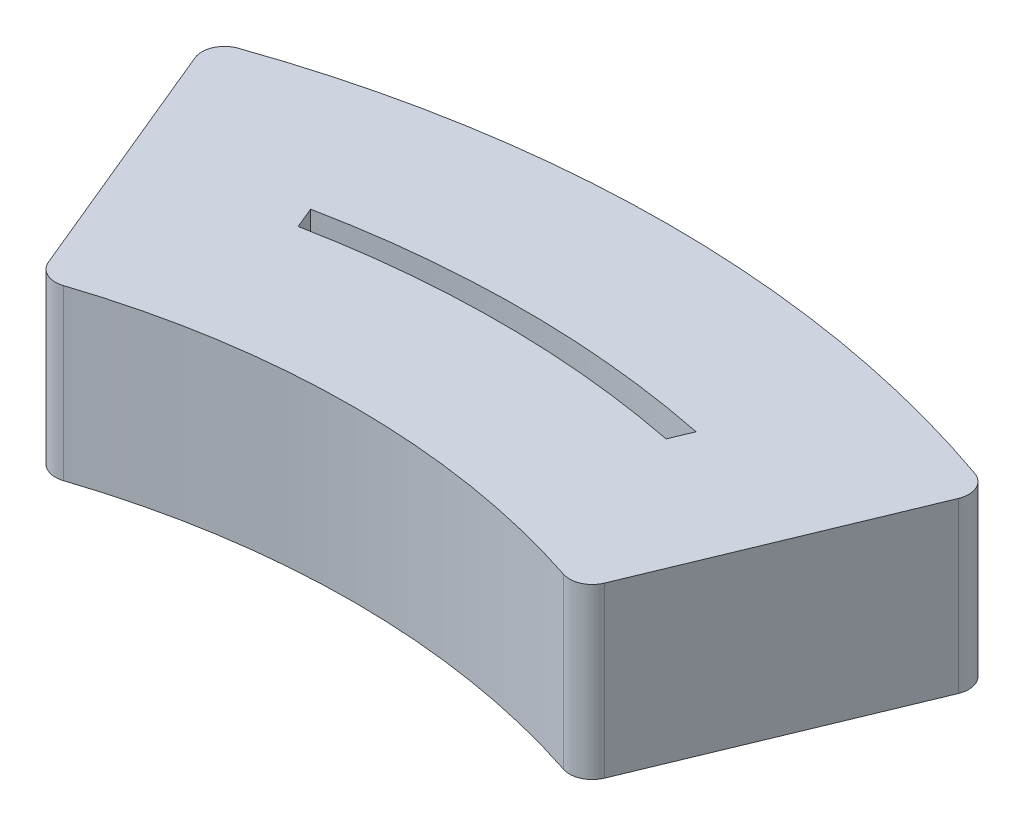
SolidWorks part; units mm, degrees
material "Copper"
ref_plane "Front Plane" through (0, 0, 0) normal (0, 0, 1) x (1, 0, 0)
ref_plane "Top Plane" through (0, 0, 0) normal (0, 1, 0) x (1, 0, 0)
ref_plane "Right Plane" through (0, 0, 0) normal (1, 0, 0) x (0, 0, -1)
sketch "Sketch1" plane through (0, 0, 0) normal (0, 1, 0) x (1, 0, 0)
  line L0 (-179.7966, 52.762) -> (-122.3696, -85.8791) construction
  line L1 (122.7764, -85.8791) -> (180.2034, 52.762) construction
  line L2 (-169.2017, 40.2491) -> (-123.1833, -70.8491)
  line L3 (123.59, -70.8491) -> (169.6084, 40.2491)
  line L4 (119.9921, -79.5351) -> (173.6131, 49.9172) construction
  line L5 (-173.2063, 49.9172) -> (-119.5854, -79.5351) construction
  line L6 (-85.3586, 7.6872) -> (-81.4581, -1.7295)
  line L7 (81.8648, -1.7295) -> (85.7653, 7.6872)
  arc A0 (-122.3696, -85.8791) -> (122.7764, -85.8791) centre (0.2034, -413.7142) cw construction
  arc A1 (180.2034, 52.762) -> (-179.7966, 52.762) centre (0.2034, -413.7142) ccw construction
  arc A2 (-110.8172, -76.5207) -> (111.2239, -76.5207) centre (0.2034, -413.7142) cw
  arc A3 (163.672, 53.5149) -> (-163.2653, 53.5149) centre (0.2034, -413.7142) ccw
  arc A4 (173.6131, 49.9172) -> (-173.2063, 49.9172) centre (0.2034, -413.7142) ccw construction
  arc A5 (163.672, 53.5149) -> (169.6084, 40.2491) centre (160.3696, 44.0759) cw
  arc A6 (-119.5854, -79.5351) -> (119.9921, -79.5351) centre (0.2034, -413.7142) cw construction
  arc A7 (123.59, -70.8491) -> (111.2239, -76.5207) centre (114.3512, -67.0223) cw
  arc A8 (-123.1833, -70.8491) -> (-110.8172, -76.5207) centre (-113.9445, -67.0223) ccw
  arc A9 (-169.2017, 40.2491) -> (-163.2653, 53.5149) centre (-159.9629, 44.0759) cw
  arc A10 (85.7653, 7.6872) -> (-85.3586, 7.6872) centre (0.2034, -413.7142) ccw
  arc A11 (-85.3586, 7.6872) -> (-85.3586, 7.6872) centre (-85.3586, 7.6872) cw
  arc A12 (-81.4581, -1.7295) -> (-81.4581, -1.7295) centre (-81.4581, -1.7295) ccw
  arc A13 (-81.4581, -1.7295) -> (81.8648, -1.7295) centre (0.2034, -413.7142) cw
  arc A14 (81.8648, -1.7295) -> (81.8648, -1.7295) centre (81.8648, -1.7295) cw
  arc A15 (85.7653, 7.6872) -> (85.7653, 7.6872) centre (85.7653, 7.6872) cw
  dimension "D2" = 10
  dimension "D1" = 5
  dimension "D3" = 65
extrude "Boss-Extrude1" add sketch "Sketch1" along normal mid plane 75
